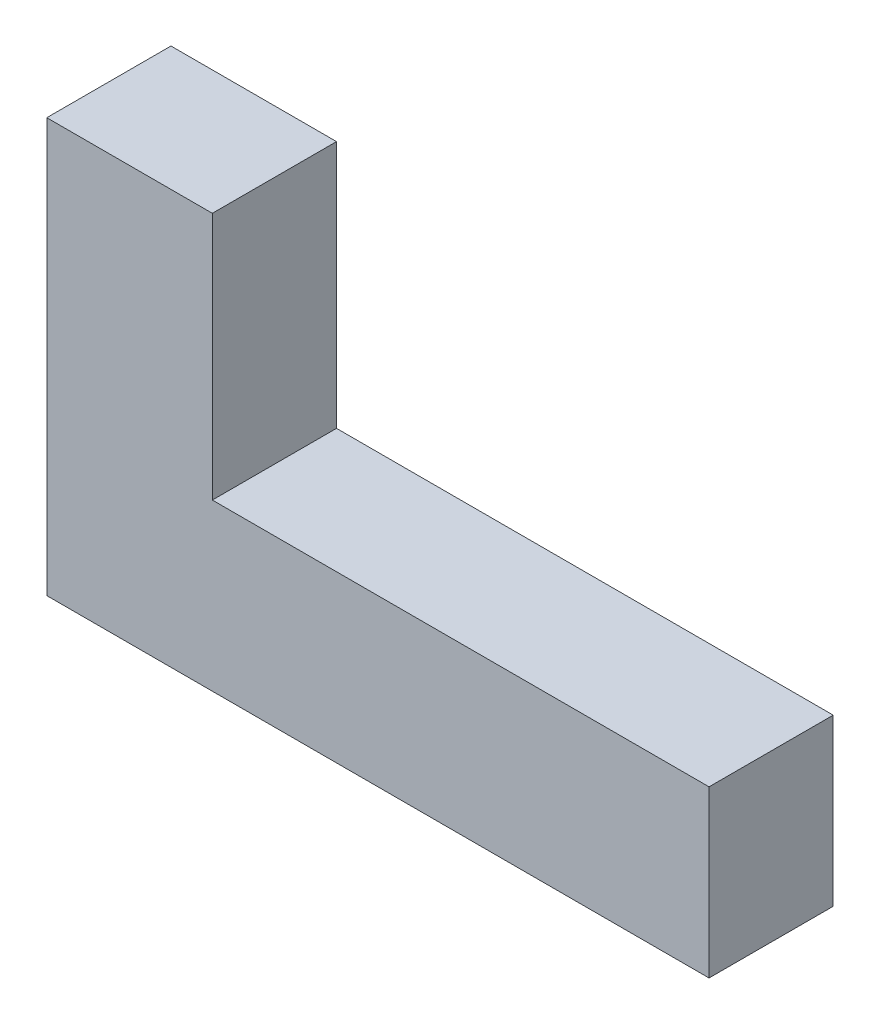
SolidWorks part; units mm, degrees
ref_plane "Front Plane" through (0, 0, 0) normal (0, 0, 1) x (1, 0, 0)
ref_plane "Top Plane" through (0, 0, 0) normal (0, 1, 0) x (1, 0, 0)
ref_plane "Right Plane" through (0, 0, 0) normal (1, 0, 0) x (0, 0, -1)
sketch "Sketch4" plane through (0, 0, 0) normal (0, 0, 1) x (1, 0, 0)
  line L0 (0, 0) -> (0, 50)
  line L1 (0, 50) -> (20, 50)
  line L2 (20, 50) -> (20, 20)
  line L3 (20, 20) -> (80, 20)
  line L4 (0, 0) -> (80, 0)
  line L5 (80, 20) -> (80, 0)
  dimension "D1" = 50
  dimension "D2" = 20
  dimension "D3" = 80
extrude "Boss-Extrude1" add sketch "Sketch4" along normal blind 15
